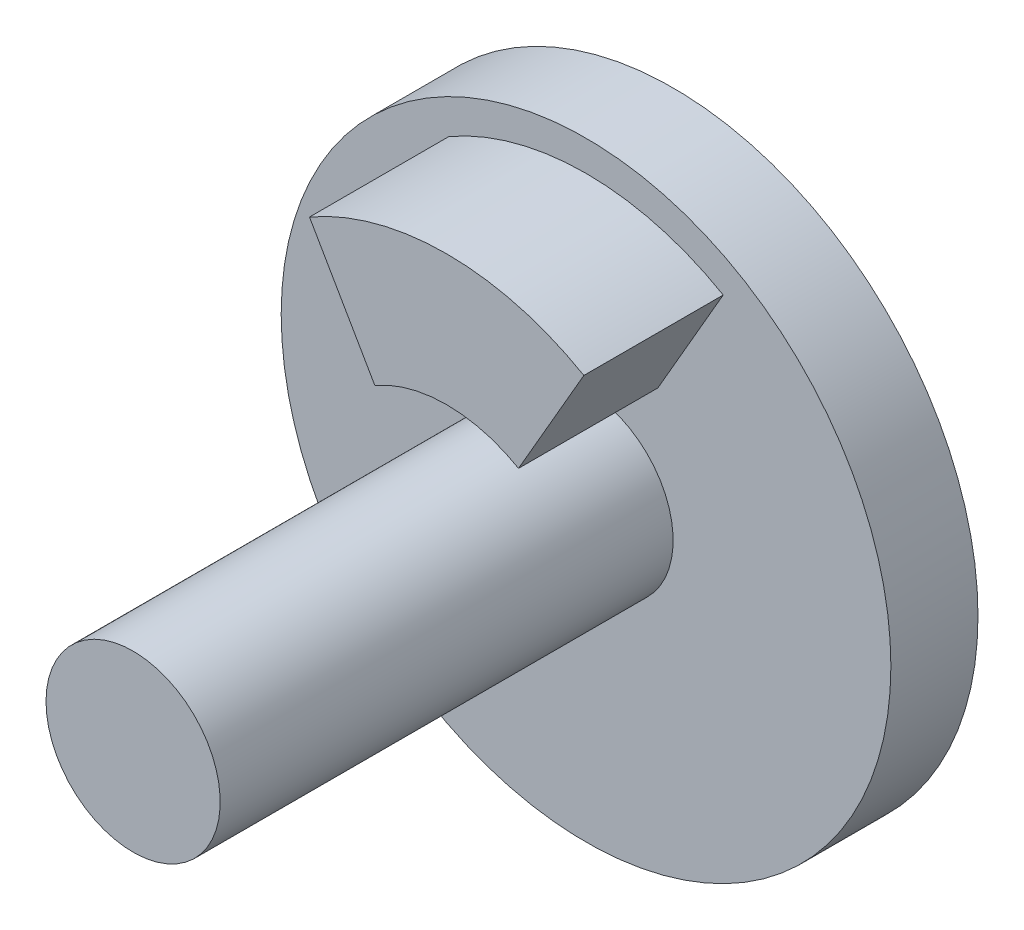
SolidWorks part; units mm, degrees
ref_plane "Front Plane" through (0, 0, 0) normal (0, 0, 1) x (1, 0, 0)
ref_plane "Top Plane" through (0, 0, 0) normal (0, 1, 0) x (1, 0, 0)
ref_plane "Right Plane" through (0, 0, 0) normal (1, 0, 0) x (0, 0, -1)
sketch "Sketch1" plane through (0, 0, 0) normal (0, 0, 1) x (1, 0, 0)
  circle A0 centre (0, 0) radius 17.5
  dimension "D1" = 35
extrude "Boss-Extrude1" add sketch "Sketch1" along normal mid plane 5
sketch "Sketch2" plane through (0, 0, 2.5) normal (0, 0, 1) x (1, 0, 0)
  line L3 (0, 0) -> (0, 11) construction
  line L4 (7.875, 13.6399) -> (4.125, 7.1447)
  line L5 (-4.125, 7.1447) -> (-7.875, 13.6399)
  arc A1 (4.125, 7.1447) -> (-4.125, 7.1447) centre (0, 0) ccw
  arc A6 (-7.875, 13.6399) -> (7.875, 13.6399) centre (0, 0) cw
  circle A7 centre (0, 0) radius 17.5 construction
  dimension "D2" = 7.5
  dimension "D3" = 1.75
  dimension "D1" = 30
extrude "Boss-Extrude2" add sketch "Sketch2" along normal blind 8
sketch "Sketch3" plane through (0, 0, 2.5) normal (0, 0, 1) x (1, 0, 0)
  circle A0 centre (0, 0) radius 5
extrude "Boss-Extrude3" add sketch "Sketch3" along normal blind 26
sketch "Sketch4" plane through (0, 0, -2.5) normal (0, 0, -1) x (-1, 0, 0)
  line L3 (-2.2361, 2) -> (2.2361, 2)
  arc A4 (-2.2361, 2) -> (2.2361, 2) centre (0, 0) ccw
  point P7 (0, 2)
extrude "Cut-Extrude1" cut sketch "Sketch4" against normal blind 10
